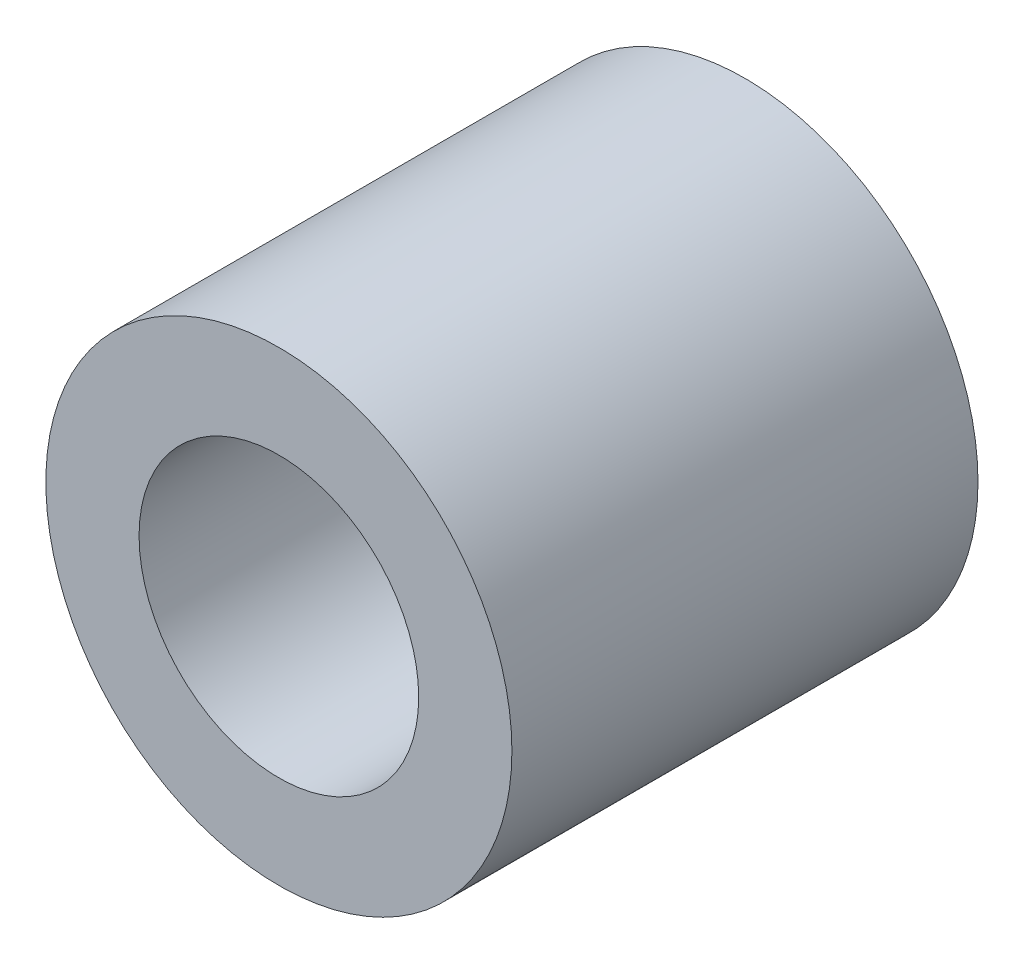
SolidWorks part; units mm, degrees
material "ASTM A36 Aço"
ref_plane "Plano frontal" through (0, 0, 0) normal (0, 0, 1) x (1, 0, 0)
ref_plane "Plano superior" through (0, 0, 0) normal (0, 1, 0) x (1, 0, 0)
ref_plane "Plano direito" through (0, 0, 0) normal (1, 0, 0) x (0, 0, -1)
sketch "Esboço1" plane through (0, 0, 0) normal (0, 0, 1) x (1, 0, 0)
  circle A0 centre (0, 0) radius 5
  circle A1 centre (0, 0) radius 3
  dimension "D1" = 10
  dimension "D2" = 6
extrude "Ressalto-extrusão1" add sketch "Esboço1" along normal blind 10
